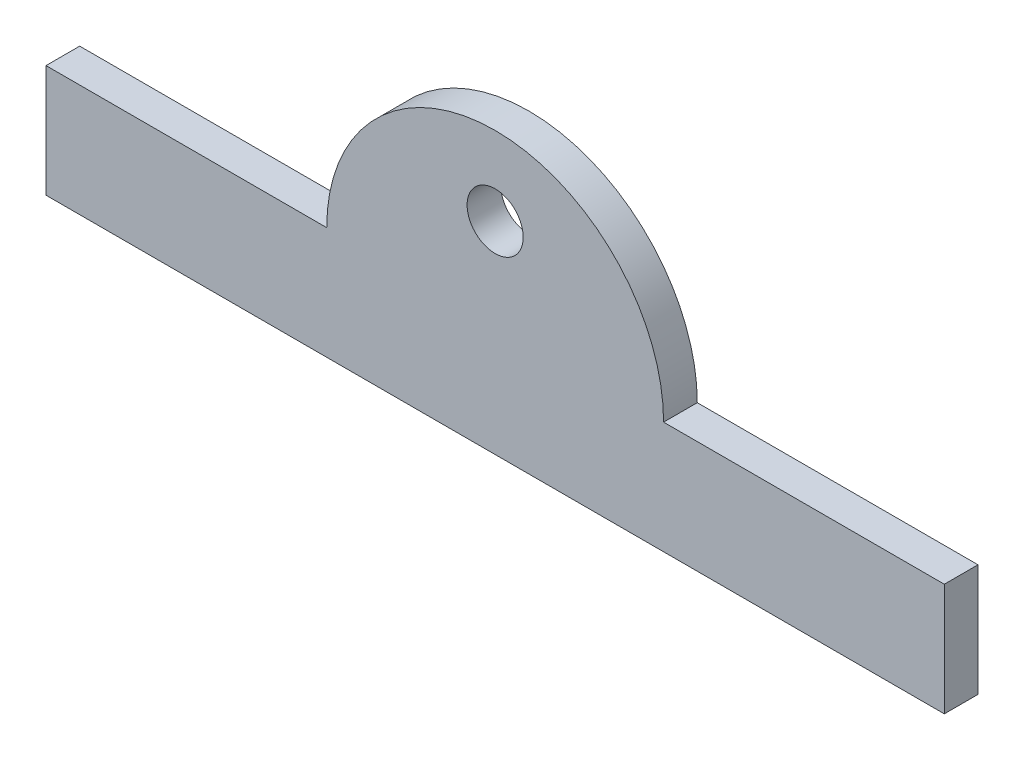
SolidWorks part; units mm, degrees
ref_plane "前视基准面" through (0, 0, 0) normal (0, 0, 1) x (1, 0, 0)
ref_plane "上视基准面" through (0, 0, 0) normal (0, 1, 0) x (1, 0, 0)
ref_plane "右视基准面" through (0, 0, 0) normal (1, 0, 0) x (0, 0, -1)
other "Configuration Table"
sketch "草图1" plane through (0, 0, 0) normal (0, 1, 0) x (1, 0, 0)
  line L1 (-40, -1.5) -> (40, -1.5)
  line L2 (-40, -1.5) -> (-40, 1.5)
  line L3 (-40, 1.5) -> (40, 1.5)
  line L4 (40, -1.5) -> (40, 1.5)
  line L5 (-40, -1.5) -> (40, 1.5) construction
  line L6 (-40, 1.5) -> (40, -1.5) construction
  point P0 (0, 0)
  dimension "D1" = 80
  dimension "D2" = 3
extrude "凸台-拉伸1" add sketch "草图1" along normal mid plane 10
sketch "草图3" plane through (0, 0, 0) normal (0, 0, 1) x (1, 0, 0)
  line L0 (-40, 5) -> (40, 5) construction
  line L1 (-15, 5) -> (15, 5)
  arc A0 (15, 5) -> (-15, 5) centre (0, 5) ccw
  circle A1 centre (0, 13) radius 2.5
  dimension "D1" = 30
  dimension "D2" = 5
  dimension "D3" = 8
extrude "凸台-拉伸2" add sketch "草图3" along normal mid plane 3
